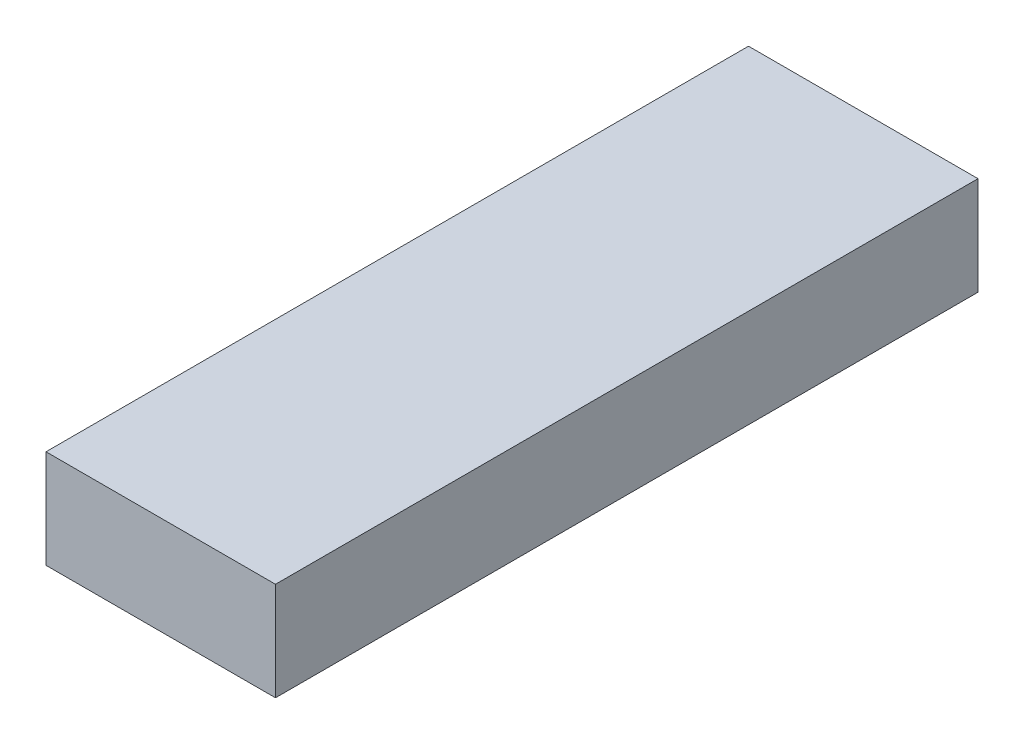
SolidWorks part; units mm, degrees
ref_plane "Plano frontal" through (0, 0, 0) normal (0, 0, 1) x (1, 0, 0)
ref_plane "Plano superior" through (0, 0, 0) normal (0, 1, 0) x (1, 0, 0)
ref_plane "Plano direito" through (0, 0, 0) normal (1, 0, 0) x (0, 0, -1)
sketch "Esboço1" plane through (0, 0, 0) normal (0, 1, 0) x (1, 0, 0)
  line L1 (-49, 150) -> (49, 150)
  line L2 (-49, 150) -> (-49, -150)
  line L3 (-49, -150) -> (49, -150)
  line L4 (49, 150) -> (49, -150)
  line L5 (-49, 150) -> (49, -150) construction
  line L6 (-49, -150) -> (49, 150) construction
  point P0 (0, 0)
  dimension "D1" = 98
  dimension "D2" = 300
extrude "Ressalto-extrusão1" add sketch "Esboço1" along normal blind 42
